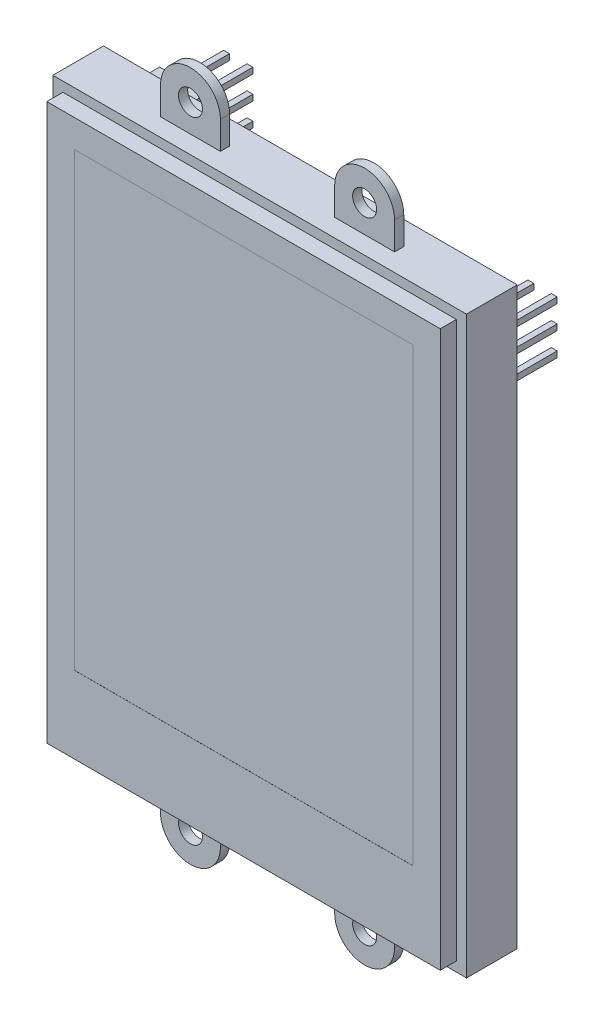
SolidWorks part; units mm, degrees
ref_plane "Plan de face" through (0, 0, 0) normal (0, 0, 1) x (1, 0, 0)
ref_plane "Plan de dessus" through (0, 0, 0) normal (0, 1, 0) x (1, 0, 0)
ref_plane "Plan de droite" through (0, 0, 0) normal (1, 0, 0) x (0, 0, -1)
ref_plane "Plan fond base" through (0, 0, 5.44) normal (0, 0, 1) x (1, 0, 0)
sketch "Esquisse1" plane through (0, 0, 5.44) normal (0, 0, 1) x (1, 0, 0)
  line L0 (-22.45, 0) -> (22.45, 0) construction
  line L1 (0, 31.2) -> (0, -31.2) construction
  line L3 (-22.45, 31.2) -> (22.45, 31.2)
  line L4 (-22.45, 31.2) -> (-22.45, -31.2)
  line L5 (-22.45, -31.2) -> (22.45, -31.2)
  line L6 (22.45, 31.2) -> (22.45, -31.2)
  point P9 (0, 31.2)
  point P10 (22.45, 0)
  dimension "D1" = 44.9
  dimension "D2" = 62.4
extrude "base plastique" add sketch "Esquisse1" along normal blind 5.5
sketch "Esquisse2" plane through (0, 0, 10.94) normal (0, 0, 1) x (1, 0, 0)
  line L0 (22.45, 31.2) -> (-22.45, 31.2) construction
  line L1 (-22.45, 31.2) -> (-22.45, -31.2) construction
  line L2 (-22.45, -31.2) -> (22.45, -31.2) construction
  line L3 (22.45, -31.2) -> (22.45, 31.2) construction
  line L12 (-21.35, 30.15) -> (-21.35, -30.15)
  line L13 (-21.35, -30.15) -> (21.35, -30.15)
  line L14 (21.35, -30.15) -> (21.35, 30.15)
  line L15 (21.35, 30.15) -> (-21.35, 30.15)
  dimension "D1" = 1.05
  dimension "D2" = 1.1
  dimension "D3" = 1.05
  dimension "D4" = 1.1
extrude "corp ecran" add sketch "Esquisse2" along normal blind 1.75
sketch "Esquisse3" plane through (0, 0, 12.69) normal (0, 0, 1) x (1, 0, 0)
  line L2 (21.35, 30.15) -> (-21.35, 30.15) construction
  line L3 (-21.35, 30.15) -> (-21.35, -30.15) construction
  line L4 (21.35, -30.15) -> (21.35, 30.15) construction
  line L5 (-21.35, -30.15) -> (21.35, -30.15) construction
  line L16 (18.37, 27.15) -> (-18.35, 27.15)
  line L17 (-18.35, 27.15) -> (-18.35, -21.81)
  line L18 (-18.35, -21.81) -> (18.37, -21.81)
  line L19 (18.37, -21.81) -> (18.37, 27.15)
  point P0 (16.8751, -11.9979)
  dimension "D1" = 48.96
  dimension "D2" = 36.72
  dimension "D3" = 3
  dimension "D4" = 3
  dimension "D5" = 2.98
  dimension "D6" = 8.34
extrude "ecran" cut sketch "Esquisse3" against normal blind 0.01
sketch "Esquisse4" plane through (0, 0, 5.44) normal (0, 0, 1) x (1, 0, 0)
  line L0 (0, 50.3439) -> (0, -52.9038) construction
  line L1 (-34.2118, 0) -> (33.0928, 0) construction
  line L2 (6.2, 34.2) -> (6.2, 31.2)
  line L3 (22.45, 31.2) -> (-22.45, 31.2) construction
  line L4 (6.2, 31.2) -> (12.7, 31.2)
  line L5 (12.7, 31.2) -> (12.7, 34.2)
  line L6 (-12.7, 31.2) -> (-12.7, 34.2)
  line L7 (-6.2, 31.2) -> (-12.7, 31.2)
  line L8 (-6.2, 34.2) -> (-6.2, 31.2)
  line L9 (6.2, -34.2) -> (6.2, -31.2)
  line L10 (6.2, -31.2) -> (12.7, -31.2)
  line L11 (12.7, -31.2) -> (12.7, -34.2)
  line L12 (-12.7, -31.2) -> (-12.7, -34.2)
  line L13 (-6.2, -31.2) -> (-12.7, -31.2)
  line L14 (-6.2, -34.2) -> (-6.2, -31.2)
  circle A0 centre (9.45, 34.2) radius 1.3
  arc A1 (6.2, 34.2) -> (12.7, 34.2) centre (9.45, 34.2) cw
  circle A2 centre (-9.45, 34.2) radius 1.3
  arc A3 (-6.2, 34.2) -> (-12.7, 34.2) centre (-9.45, 34.2) ccw
  arc A4 (6.2, -34.2) -> (12.7, -34.2) centre (9.45, -34.2) ccw
  arc A5 (-6.2, -34.2) -> (-12.7, -34.2) centre (-9.45, -34.2) cw
  circle A6 centre (-9.45, -34.2) radius 1.3
  circle A7 centre (9.45, -34.2) radius 1.3
  point P29 (9.45, 37.45)
  point P30 (0, 0)
  dimension "D7" = 2.6
  dimension "D1" = 3
  dimension "D3" = 18.9
  dimension "D4" = 6.5
  dimension "D6" = 68.4
extrude "oreilles" add sketch "Esquisse4" along normal blind 1 from offset 2.56
sketch "Esquisse5" plane through (0, 0, 5.44) normal (0, 0, -1) x (-1, 0, 0)
  line L0 (15.77, 28.1) -> (15.13, 28.1) construction
  line L1 (15.13, 28.42) -> (15.77, 28.42)
  line L2 (15.13, 28.42) -> (15.13, 27.78)
  line L3 (15.13, 27.78) -> (15.77, 27.78)
  line L4 (15.77, 28.42) -> (15.77, 27.78)
  line L5 (15.45, 28.42) -> (15.45, 27.78) construction
  line L6 (17.67, 27.78) -> (18.31, 27.78)
  line L7 (18.31, 28.42) -> (18.31, 27.78)
  line L8 (17.67, 28.42) -> (18.31, 28.42)
  line L9 (17.67, 28.42) -> (17.67, 27.78)
  line L10 (15.13, 25.24) -> (15.77, 25.24)
  line L11 (15.77, 25.88) -> (15.77, 25.24)
  line L12 (15.13, 25.88) -> (15.77, 25.88)
  line L13 (15.13, 25.88) -> (15.13, 25.24)
  line L14 (17.67, 25.24) -> (18.31, 25.24)
  line L15 (18.31, 25.88) -> (18.31, 25.24)
  line L16 (17.67, 25.88) -> (18.31, 25.88)
  line L17 (17.67, 25.88) -> (17.67, 25.24)
  line L18 (15.13, 22.7) -> (15.77, 22.7)
  line L19 (15.77, 23.34) -> (15.77, 22.7)
  line L20 (15.13, 23.34) -> (15.77, 23.34)
  line L21 (15.13, 23.34) -> (15.13, 22.7)
  line L22 (17.67, 22.7) -> (18.31, 22.7)
  line L23 (18.31, 23.34) -> (18.31, 22.7)
  line L24 (17.67, 23.34) -> (18.31, 23.34)
  line L25 (17.67, 23.34) -> (17.67, 22.7)
  line L26 (15.13, 20.16) -> (15.77, 20.16)
  line L27 (15.77, 20.8) -> (15.77, 20.16)
  line L28 (15.13, 20.8) -> (15.77, 20.8)
  line L29 (15.13, 20.8) -> (15.13, 20.16)
  line L30 (17.67, 20.16) -> (18.31, 20.16)
  line L31 (18.31, 20.8) -> (18.31, 20.16)
  line L32 (17.67, 20.8) -> (18.31, 20.8)
  line L33 (17.67, 20.8) -> (17.67, 20.16)
  line L34 (15.13, 17.62) -> (15.77, 17.62)
  line L35 (15.77, 18.26) -> (15.77, 17.62)
  line L36 (15.13, 18.26) -> (15.77, 18.26)
  line L37 (15.13, 18.26) -> (15.13, 17.62)
  line L38 (17.67, 17.62) -> (18.31, 17.62)
  line L39 (18.31, 18.26) -> (18.31, 17.62)
  line L40 (17.67, 18.26) -> (18.31, 18.26)
  line L41 (17.67, 18.26) -> (17.67, 17.62)
  line L42 (15.13, 15.08) -> (15.77, 15.08)
  line L43 (15.77, 15.72) -> (15.77, 15.08)
  line L44 (15.13, 15.72) -> (15.77, 15.72)
  line L45 (15.13, 15.72) -> (15.13, 15.08)
  line L46 (17.67, 15.08) -> (18.31, 15.08)
  line L47 (18.31, 15.72) -> (18.31, 15.08)
  line L48 (17.67, 15.72) -> (18.31, 15.72)
  line L49 (17.67, 15.72) -> (17.67, 15.08)
  line L50 (15.13, 12.54) -> (15.77, 12.54)
  line L51 (15.77, 13.18) -> (15.77, 12.54)
  line L52 (15.13, 13.18) -> (15.77, 13.18)
  line L53 (15.13, 13.18) -> (15.13, 12.54)
  line L54 (17.67, 12.54) -> (18.31, 12.54)
  line L55 (18.31, 13.18) -> (18.31, 12.54)
  line L56 (17.67, 13.18) -> (18.31, 13.18)
  line L57 (17.67, 13.18) -> (17.67, 12.54)
  line L58 (15.13, 10) -> (15.77, 10)
  line L59 (15.77, 10.64) -> (15.77, 10)
  line L60 (15.13, 10.64) -> (15.77, 10.64)
  line L61 (15.13, 10.64) -> (15.13, 10)
  line L62 (17.67, 10) -> (18.31, 10)
  line L63 (18.31, 10.64) -> (18.31, 10)
  line L64 (17.67, 10.64) -> (18.31, 10.64)
  line L65 (17.67, 10.64) -> (17.67, 10)
  line L66 (15.13, 7.46) -> (15.77, 7.46)
  line L67 (15.77, 8.1) -> (15.77, 7.46)
  line L68 (15.13, 8.1) -> (15.77, 8.1)
  line L69 (15.13, 8.1) -> (15.13, 7.46)
  line L70 (17.67, 7.46) -> (18.31, 7.46)
  line L71 (18.31, 8.1) -> (18.31, 7.46)
  line L72 (17.67, 8.1) -> (18.31, 8.1)
  line L73 (17.67, 8.1) -> (17.67, 7.46)
  line L74 (15.13, 4.92) -> (15.77, 4.92)
  line L75 (15.77, 5.56) -> (15.77, 4.92)
  line L76 (15.13, 5.56) -> (15.77, 5.56)
  line L77 (15.13, 5.56) -> (15.13, 4.92)
  line L78 (17.67, 4.92) -> (18.31, 4.92)
  line L79 (18.31, 5.56) -> (18.31, 4.92)
  line L80 (17.67, 5.56) -> (18.31, 5.56)
  line L81 (17.67, 5.56) -> (17.67, 4.92)
  line L82 (15.13, 2.38) -> (15.77, 2.38)
  line L83 (15.77, 3.02) -> (15.77, 2.38)
  line L84 (15.13, 3.02) -> (15.77, 3.02)
  line L85 (15.13, 3.02) -> (15.13, 2.38)
  line L86 (17.67, 2.38) -> (18.31, 2.38)
  line L87 (18.31, 3.02) -> (18.31, 2.38)
  line L88 (17.67, 3.02) -> (18.31, 3.02)
  line L89 (17.67, 3.02) -> (17.67, 2.38)
  line L90 (15.13, -0.16) -> (15.77, -0.16)
  line L91 (15.77, 0.48) -> (15.77, -0.16)
  line L92 (15.13, 0.48) -> (15.77, 0.48)
  line L93 (15.13, 0.48) -> (15.13, -0.16)
  line L94 (17.67, -0.16) -> (18.31, -0.16)
  line L95 (18.31, 0.48) -> (18.31, -0.16)
  line L96 (17.67, 0.48) -> (18.31, 0.48)
  line L97 (17.67, 0.48) -> (17.67, -0.16)
  line L98 (15.13, -2.7) -> (15.77, -2.7)
  line L99 (15.77, -2.06) -> (15.77, -2.7)
  line L100 (15.13, -2.06) -> (15.77, -2.06)
  line L101 (15.13, -2.06) -> (15.13, -2.7)
  line L102 (17.67, -2.7) -> (18.31, -2.7)
  line L103 (18.31, -2.06) -> (18.31, -2.7)
  line L104 (17.67, -2.06) -> (18.31, -2.06)
  line L105 (17.67, -2.06) -> (17.67, -2.7)
  line L106 (15.13, -5.24) -> (15.77, -5.24)
  line L107 (15.77, -4.6) -> (15.77, -5.24)
  line L108 (15.13, -4.6) -> (15.77, -4.6)
  line L109 (15.13, -4.6) -> (15.13, -5.24)
  line L110 (17.67, -5.24) -> (18.31, -5.24)
  line L111 (18.31, -4.6) -> (18.31, -5.24)
  line L112 (17.67, -4.6) -> (18.31, -4.6)
  line L113 (17.67, -4.6) -> (17.67, -5.24)
  line L114 (15.13, -7.78) -> (15.77, -7.78)
  line L115 (15.77, -7.14) -> (15.77, -7.78)
  line L116 (15.13, -7.14) -> (15.77, -7.14)
  line L117 (15.13, -7.14) -> (15.13, -7.78)
  line L118 (17.67, -7.78) -> (18.31, -7.78)
  line L119 (18.31, -7.14) -> (18.31, -7.78)
  line L120 (17.67, -7.14) -> (18.31, -7.14)
  line L121 (17.67, -7.14) -> (17.67, -7.78)
  line L122 (15.13, -10.32) -> (15.77, -10.32) [skipped]
  line L123 (15.77, -9.68) -> (15.77, -10.32) [skipped]
  line L124 (15.13, -9.68) -> (15.77, -9.68) [skipped]
  line L125 (15.13, -9.68) -> (15.13, -10.32) [skipped]
  line L126 (17.67, -10.32) -> (18.31, -10.32) [skipped]
  line L127 (18.31, -9.68) -> (18.31, -10.32) [skipped]
  line L128 (17.67, -9.68) -> (18.31, -9.68) [skipped]
  line L129 (17.67, -9.68) -> (17.67, -10.32) [skipped]
  line L130 (15.13, -12.86) -> (15.77, -12.86)
  line L131 (15.77, -12.22) -> (15.77, -12.86)
  line L132 (15.13, -12.22) -> (15.77, -12.22)
  line L133 (15.13, -12.22) -> (15.13, -12.86)
  line L134 (17.67, -12.86) -> (18.31, -12.86)
  line L135 (18.31, -12.22) -> (18.31, -12.86)
  line L136 (17.67, -12.22) -> (18.31, -12.22)
  line L137 (17.67, -12.22) -> (17.67, -12.86)
  line L138 (15.13, -15.4) -> (15.77, -15.4)
  line L139 (15.77, -14.76) -> (15.77, -15.4)
  line L140 (15.13, -14.76) -> (15.77, -14.76)
  line L141 (15.13, -14.76) -> (15.13, -15.4)
  line L142 (17.67, -15.4) -> (18.31, -15.4)
  line L143 (18.31, -14.76) -> (18.31, -15.4)
  line L144 (17.67, -14.76) -> (18.31, -14.76)
  line L145 (17.67, -14.76) -> (17.67, -15.4)
  line L146 (15.13, -17.94) -> (15.77, -17.94)
  line L147 (15.77, -17.3) -> (15.77, -17.94)
  line L148 (15.13, -17.3) -> (15.77, -17.3)
  line L149 (15.13, -17.3) -> (15.13, -17.94)
  line L150 (17.67, -17.94) -> (18.31, -17.94)
  line L151 (18.31, -17.3) -> (18.31, -17.94)
  line L152 (17.67, -17.3) -> (18.31, -17.3)
  line L153 (17.67, -17.3) -> (17.67, -17.94)
  line L154 (15.13, -20.48) -> (15.77, -20.48)
  line L155 (15.77, -19.84) -> (15.77, -20.48)
  line L156 (15.13, -19.84) -> (15.77, -19.84)
  line L157 (15.13, -19.84) -> (15.13, -20.48)
  line L158 (17.67, -20.48) -> (18.31, -20.48)
  line L159 (18.31, -19.84) -> (18.31, -20.48)
  line L160 (17.67, -19.84) -> (18.31, -19.84)
  line L161 (17.67, -19.84) -> (17.67, -20.48)
  line L162 (15.13, -23.02) -> (15.77, -23.02)
  line L163 (15.77, -22.38) -> (15.77, -23.02)
  line L164 (15.13, -22.38) -> (15.77, -22.38)
  line L165 (15.13, -22.38) -> (15.13, -23.02)
  line L166 (17.67, -23.02) -> (18.31, -23.02)
  line L167 (18.31, -22.38) -> (18.31, -23.02)
  line L168 (17.67, -22.38) -> (18.31, -22.38)
  line L169 (17.67, -22.38) -> (17.67, -23.02)
  line L170 (15.13, 27.78) -> (17.67, 27.78) construction
  line L171 (15.13, 27.78) -> (15.13, 25.24) construction
  line L172 (0.21, 64.3897) -> (0.21, -25.1414) construction
  line L173 (-17.25, 18.26) -> (-17.25, 17.62)
  line L174 (-17.25, 18.26) -> (-17.89, 18.26)
  line L175 (-17.89, 18.26) -> (-17.89, 17.62)
  line L176 (-17.25, 17.62) -> (-17.89, 17.62)
  line L177 (-14.71, 18.26) -> (-14.71, 17.62)
  line L178 (-14.71, 18.26) -> (-15.35, 18.26)
  line L179 (-15.35, 18.26) -> (-15.35, 17.62)
  line L180 (-14.71, 17.62) -> (-15.35, 17.62)
  line L181 (-17.25, 20.8) -> (-17.25, 20.16)
  line L182 (-17.25, 20.8) -> (-17.89, 20.8)
  line L183 (-17.89, 20.8) -> (-17.89, 20.16)
  line L184 (-17.25, 20.16) -> (-17.89, 20.16)
  line L185 (-14.71, 20.8) -> (-14.71, 20.16)
  line L186 (-14.71, 20.8) -> (-15.35, 20.8)
  line L187 (-15.35, 20.8) -> (-15.35, 20.16)
  line L188 (-14.71, 20.16) -> (-15.35, 20.16)
  line L189 (-17.25, 23.34) -> (-17.25, 22.7)
  line L190 (-17.25, 23.34) -> (-17.89, 23.34)
  line L191 (-17.89, 23.34) -> (-17.89, 22.7)
  line L192 (-17.25, 22.7) -> (-17.89, 22.7)
  line L193 (-14.71, 23.34) -> (-14.71, 22.7)
  line L194 (-14.71, 23.34) -> (-15.35, 23.34)
  line L195 (-15.35, 23.34) -> (-15.35, 22.7)
  line L196 (-14.71, 22.7) -> (-15.35, 22.7)
  line L197 (-15.03, 23.34) -> (-15.03, 22.7) construction
  dimension "D1" = 6
  dimension "D2" = 6.1
  dimension "D3" = 0.64
  dimension "D4" = 2.54
  dimension "D5" = 2.54
  dimension "D6" = 30.48
extrude "pins" add sketch "Esquisse5" along normal blind 8.9
sketch "Esquisse6" plane through (0, 0, 5.44) normal (0, 0, -1) x (-1, 0, 0)
  line L0 (15.77, 28.42) -> (15.13, 28.42) construction
  line L1 (14.18, 29.37) -> (19.26, 29.37)
  line L2 (14.18, 29.37) -> (14.18, -8.73)
  line L3 (14.18, -8.73) -> (19.26, -8.73)
  line L4 (19.26, 29.37) -> (19.26, -8.73)
  line L5 (-18.84, 24.29) -> (-13.76, 24.29)
  line L6 (-18.84, 24.29) -> (-18.84, 16.67)
  line L7 (-18.84, 16.67) -> (-13.76, 16.67)
  line L8 (-13.76, 24.29) -> (-13.76, 16.67)
  line L9 (18.31, 27.78) -> (18.31, 28.42) construction
  line L10 (18.31, -23.02) -> (18.31, -22.38) construction
  line L11 (-17.89, 18.26) -> (-17.89, 17.62) construction
  line L13 (-17.89, 23.34) -> (-17.89, 22.7) construction
  line L14 (-17.25, 23.34) -> (-17.89, 23.34) construction
  line L16 (18.31, -7.78) -> (18.31, -7.14) construction
  line L17 (18.31, -12.86) -> (18.31, -12.22) construction
  line L18 (14.18, -11.27) -> (19.26, -11.27)
  line L19 (14.18, -11.27) -> (14.18, -23.97)
  line L20 (14.18, -23.97) -> (19.26, -23.97)
  line L21 (19.26, -11.27) -> (19.26, -23.97)
  point P8 (15.45, 28.42)
  point P11 (18.31, 28.1)
  point P17 (-17.89, 17.94)
  point P20 (-17.57, 23.34)
  point P22 (-17.89, 23.02)
  point P28 (18.31, -7.46)
  point P33 (18.31, -12.54)
  point P36 (18.31, -22.7)
  dimension "D1" = 5.08
  dimension "D2" = 1.27
  dimension "D3" = 1.27
  dimension "D4" = 1.27
  dimension "D5" = 1.27
  dimension "D6" = 1.27
  dimension "D7" = 1.27
  dimension "D8" = 1.27
  dimension "D9" = 1.27
extrude "plastique connecteurs" add sketch "Esquisse6" along normal blind 2.9
